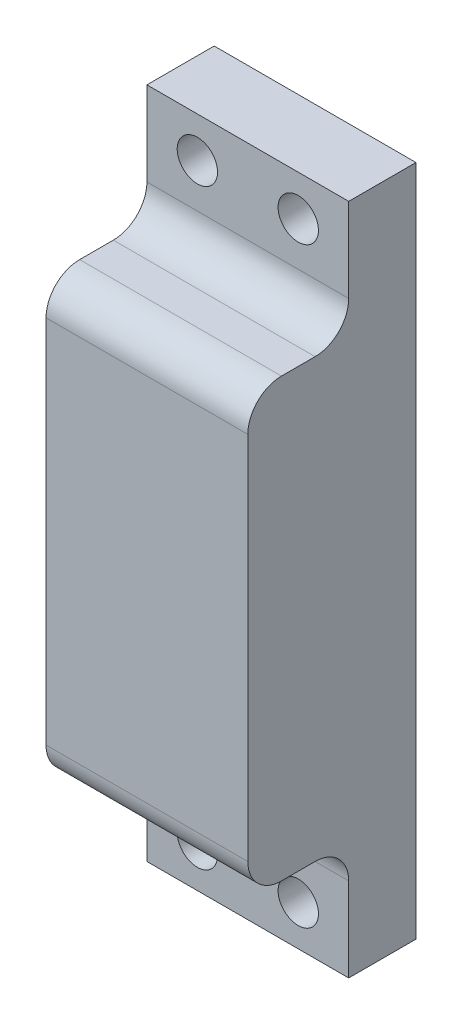
SolidWorks part; units mm, degrees
ref_plane "Front Plane" through (0, 0, 0) normal (1, 0, 0) x (0, 1, 0)
ref_plane "Top Plane" through (0, 0, 0) normal (0, 0, 1) x (0, 1, 0)
ref_plane "Right Plane" through (0, 0, 0) normal (0, 1, 0) x (-1, 0, 0)
sketch "Sketch1" plane through (0, 0, 0) normal (1, 0, 0) x (0, 1, 0)
  line L0 (-100, 0) -> (100, 0)
  line L1 (100, 0) -> (100, 20)
  line L2 (100, 20) -> (75, 20)
  line L3 (65, 30) -> (65, 40)
  line L4 (55, 50) -> (-55, 50)
  line L5 (-65, 40) -> (-65, 30)
  line L6 (-75, 20) -> (-100, 20)
  line L7 (-100, 20) -> (-100, 0)
  arc A0 (65, 40) -> (55, 50) centre (55, 40) ccw
  arc A1 (75, 20) -> (65, 30) centre (75, 30) cw
  arc A2 (-55, 50) -> (-65, 40) centre (-55, 40) ccw
  arc A3 (-65, 30) -> (-75, 20) centre (-75, 30) cw
  point P3 (0, 0)
  point P18 (-65, 20)
  dimension "D5" = 10
  dimension "D1" = 200
  dimension "D2" = 130
  dimension "D3" = 50
  dimension "D4" = 35
  dimension "D6" = 20
extrude "Boss-Extrude1" add sketch "Sketch1" against normal blind 60
hole_wizard "CBORE for M10 Hex Head Bolt1" positions "Sketch2" profile "Sketch3" counterbore size "M10" standard "ANSI Metric" end condition through all
sketch "Sketch2" plane through (0, 0, 20) normal (0, 0, 1) x (1, 0, 0)
  line L0 (0, -75) -> (0, -100) construction
  line L1 (-60, -100) -> (0, -100) construction
  line L2 (-60, 100) -> (0, 100) construction
  point P0 (-15, -88)
  point P2 (-45, -88)
  point P4 (-45, 88)
  point P6 (-15, 88)
  point P15 (-8.4921, -97.2335)
  point P18 (0, 0)
  point P19 (0, 0)
  point P20 (0, 0)
  point P21 (-45, 87.9538)
  point P22 (-45, -88)
  point P23 (-45, -88)
  dimension "D1" = 30
  dimension "D2" = 15
  dimension "D3" = 12
  dimension "D4" = 12
sketch "Sketch3" plane through (-15, -88, 20) normal (1, 0, 0) x (0, -1, 0)
  line L0 (0, 0) -> (0, 20)
  line L1 (0, 20) -> (4, 20)
  line L3 (4, 20) -> (4, 10)
  line L4 (4, 10) -> (6, 10)
  line L5 (6, 10) -> (6, 0)
  line L7 (6, 0) -> (0, 0)
  line L11 (0, -6.35) -> (0, 107.95) construction
  dimension "Thru Hole Dia." = 8
  dimension "Thru Hole Depth" = 20
  dimension "C'Bore Dia." = 12
  dimension "C'Bore Depth" = 10
